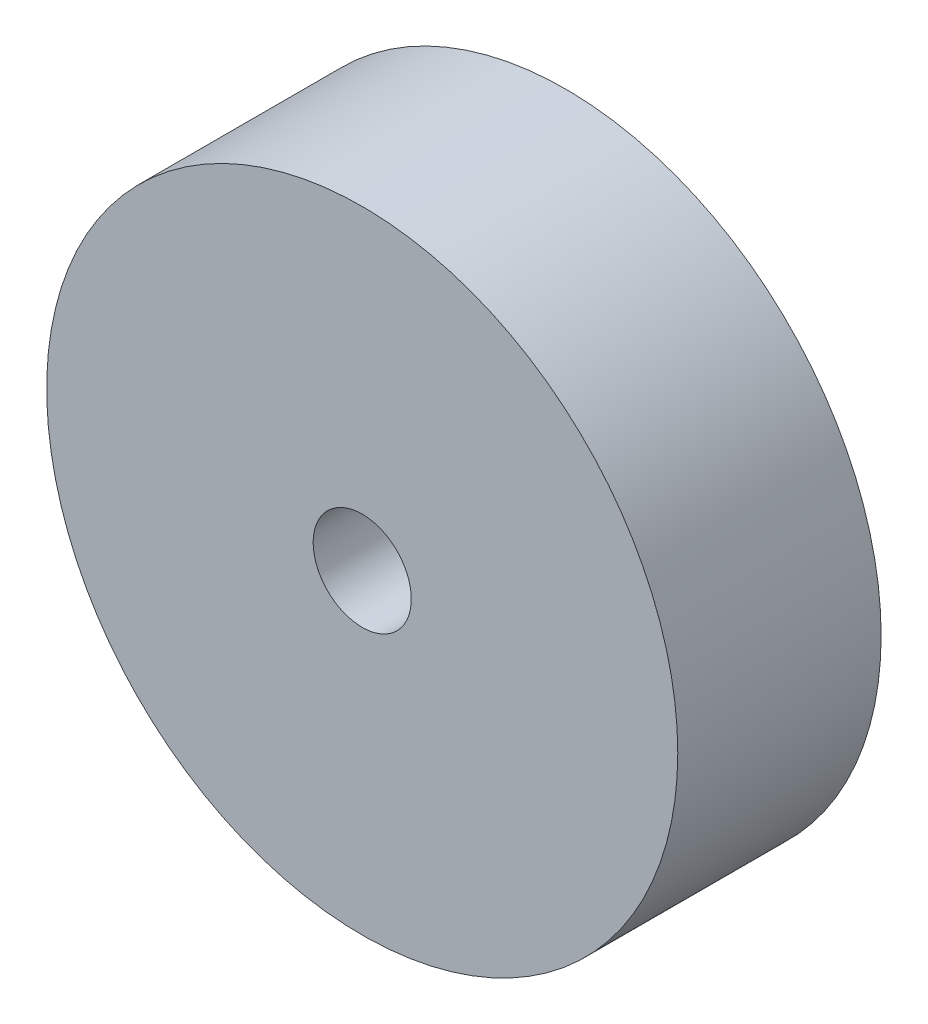
SolidWorks part; units mm, degrees
ref_plane "Front Plane" through (0, 0, 0) normal (0, 0, 1) x (1, 0, 0)
ref_plane "Top Plane" through (0, 0, 0) normal (0, 1, 0) x (1, 0, 0)
ref_plane "Right Plane" through (0, 0, 0) normal (1, 0, 0) x (0, 0, -1)
sketch "Sketch1" plane through (0, 0, 0) normal (0, 0, 1) x (1, 0, 0)
  circle A0 centre (-29.0823, -1.7038) radius 9
  dimension "D1" = 18
extrude "Boss-Extrude1" add sketch "Sketch1" along normal blind 5.8
sketch "Sketch2" plane through (0, 0, 0) normal (0, 0, -1) x (-1, 0, 0)
  circle A0 centre (29.0823, -1.7038) radius 6.4
  dimension "D1" = 12.8
extrude "Cut-Extrude1" cut sketch "Sketch2" against normal blind 3.2
sketch "Sketch3" plane through (0, 0, 3.2) normal (0, 0, -1) x (-1, 0, 0)
  circle A0 centre (29.0823, -1.7038) radius 1
  dimension "D1" = 2
extrude "Boss-Extrude2" add sketch "Sketch3" along normal blind 3
sketch "Sketch4" plane through (0, 0, 0.2) normal (0, 0, -1) x (-1, 0, 0)
  circle A0 centre (29.0823, -1.7038) radius 3.15
  dimension "D1" = 6.3
extrude "Boss-Extrude3" add sketch "Sketch4" against normal blind 3
sketch "Sketch5" plane through (0, 0, 0.2) normal (0, 0, -1) x (-1, 0, 0)
  circle A0 centre (29.0823, -1.7038) radius 1.4
  dimension "D1" = 2.8
extrude "Cut-Extrude2" cut sketch "Sketch5" against normal through all
